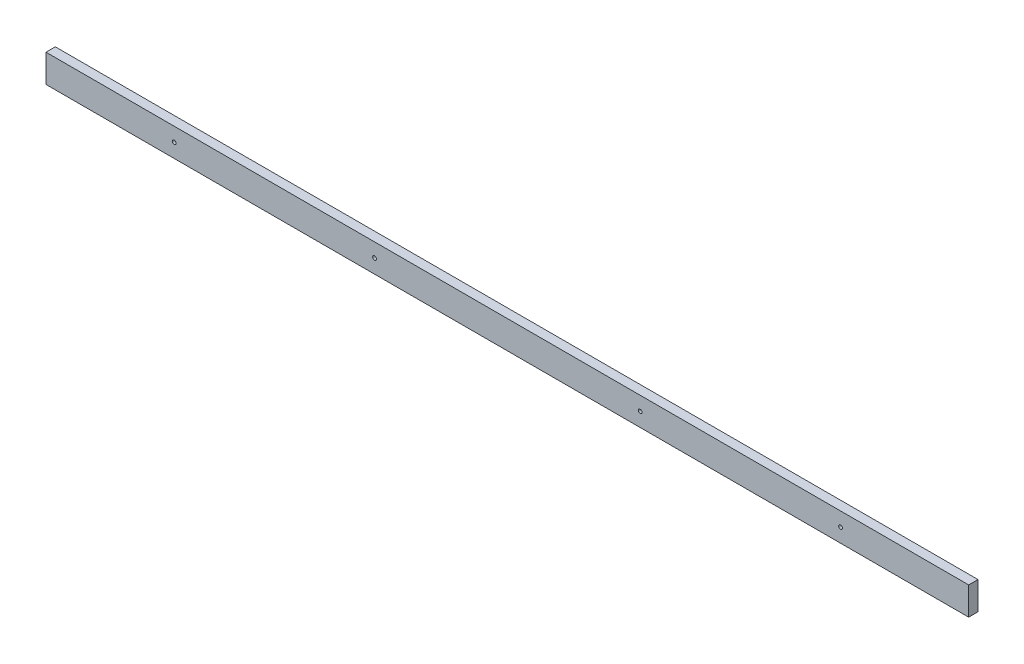
SolidWorks part; units mm, degrees
ref_plane "Спереди" through (0, 0, 0) normal (0, 0, 1) x (1, 0, 0)
ref_plane "Сверху" through (0, 0, 0) normal (0, 1, 0) x (1, 0, 0)
ref_plane "Справа" through (0, 0, 0) normal (1, 0, 0) x (0, 0, -1)
sketch "Эскиз1" plane through (0, 0, 0) normal (0, 0, 1) x (1, 0, 0)
  line L1 (-990, 30) -> (990, 30)
  line L2 (-990, 30) -> (-990, -30)
  line L3 (-990, -30) -> (990, -30)
  line L4 (990, 30) -> (990, -30)
  line L5 (-990, 30) -> (990, -30) construction
  line L6 (-990, -30) -> (990, 30) construction
  point P0 (0, 0)
  dimension "D1" = 1980
  dimension "D2" = 60
extrude "Бобышка-Вытянуть1" add sketch "Эскиз1" along normal mid plane 20
sketch "Эскиз2" plane through (0, 0, 0) normal (0, 0, 1) x (1, 0, 0)
  line L0 (-1057.2071, 0) -> (1092.0376, 0) construction
  line L1 (-990, 30) -> (-990, -30) construction
  line L2 (0, 174.5853) -> (0, -190.4559) construction
  circle A0 centre (-715, 0) radius 4
  circle A1 centre (-285, 0) radius 4
  circle A2 centre (285, 0) radius 4
  circle A3 centre (715, 0) radius 4
  dimension "D2" = 8
  dimension "D1" = 275
  dimension "D3" = 430
extrude "Вырез-Вытянуть1" cut sketch "Эскиз2" against normal through all and the other way through all
